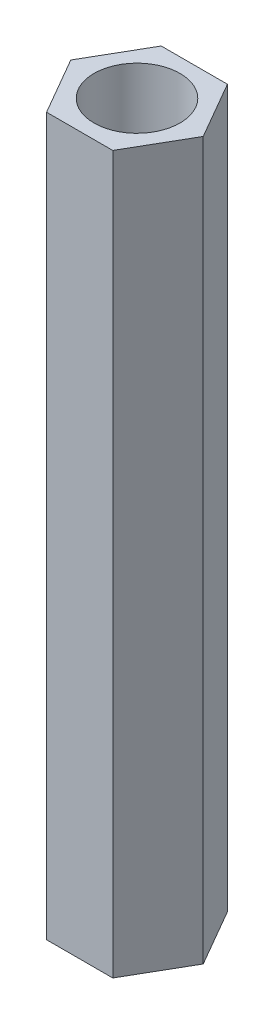
SolidWorks part; units mm, degrees
ref_plane "Front Plane" through (0, 0, 0) normal (0, 0, 1) x (1, 0, 0)
ref_plane "Top Plane" through (0, 0, 0) normal (0, 1, 0) x (1, 0, 0)
ref_plane "Right Plane" through (0, 0, 0) normal (1, 0, 0) x (0, 0, -1)
sketch "草图1" plane through (0, 0, 0) normal (0, 1, 0) x (1, 0, 0)
  line L1 (2.3094, 0) -> (1.1547, 2)
  line L2 (1.1547, 2) -> (-1.1547, 2)
  line L3 (-1.1547, 2) -> (-2.3094, 0)
  line L4 (-2.3094, 0) -> (-1.1547, -2)
  line L5 (-1.1547, -2) -> (1.1547, -2)
  line L6 (1.1547, -2) -> (2.3094, 0)
  circle A0 centre (0, 0) radius 2 construction
  dimension "D1" = 4
extrude "凸台-拉伸1" add sketch "草图1" along normal blind 25
sketch "草图2" plane through (0, 25, 0) normal (0, 1, 0) x (1, 0, 0)
  circle A0 centre (0, 0) radius 1.5
  dimension "D1" = 3
extrude "切除-拉伸1" cut sketch "草图2" against normal through all
